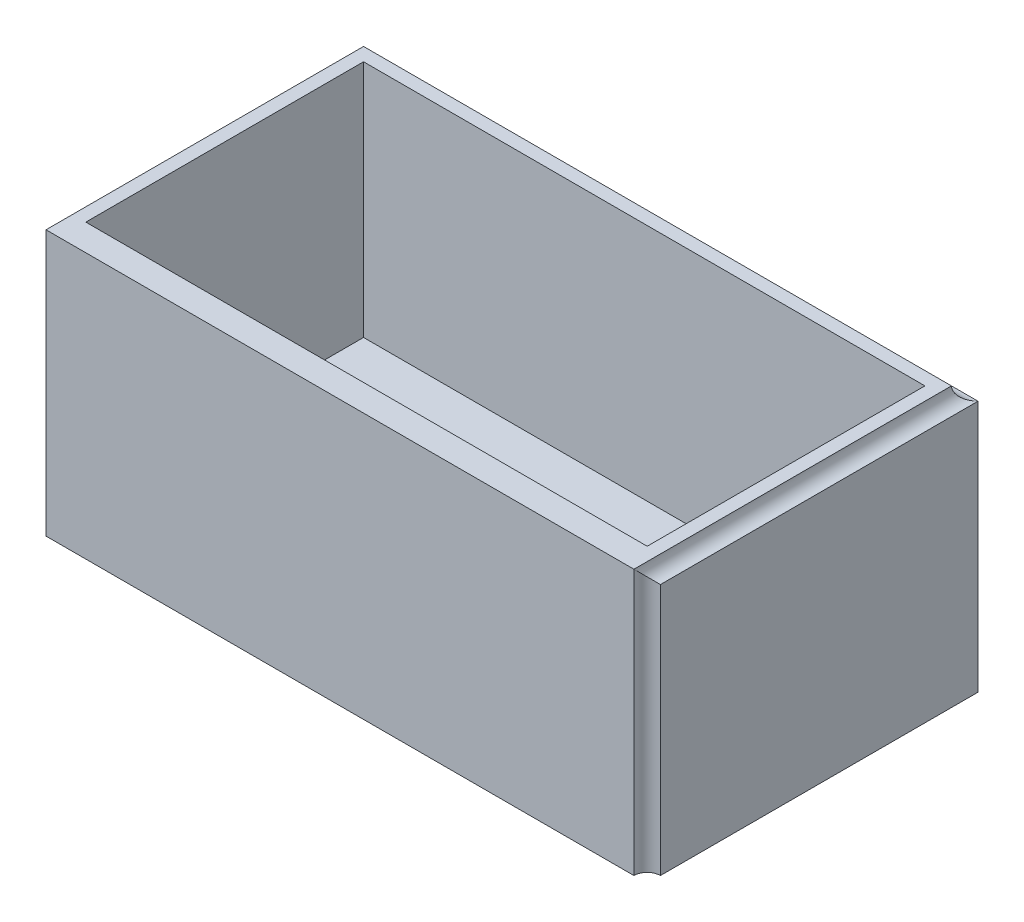
SolidWorks part; units mm, degrees
ref_plane "前视基准面" through (0, 0, 0) normal (0, 0, 1) x (1, 0, 0)
ref_plane "上视基准面" through (0, 0, 0) normal (0, 1, 0) x (1, 0, 0)
ref_plane "右视基准面" through (0, 0, 0) normal (1, 0, 0) x (0, 0, -1)
other "Configuration Table"
sketch "草图1" plane through (0, 0, 0) normal (0, 1, 0) x (1, 0, 0)
  line L1 (-116.4574, 65.3521) -> (115.1504, 65.3521)
  line L2 (-116.4574, 65.3521) -> (-116.4574, -59.3397)
  line L3 (-116.4574, -59.3397) -> (115.1504, -59.3397)
  line L4 (115.1504, 65.3521) -> (115.1504, -59.3397)
extrude "凸台-拉伸1" add sketch "草图1" along normal mid plane 100
shell "抽壳1" thickness 10
curve "组合曲线1"
sweep "切除-扫描1" cut path "组合曲线1" circular profile diameter 10 parameters "D3"=10
